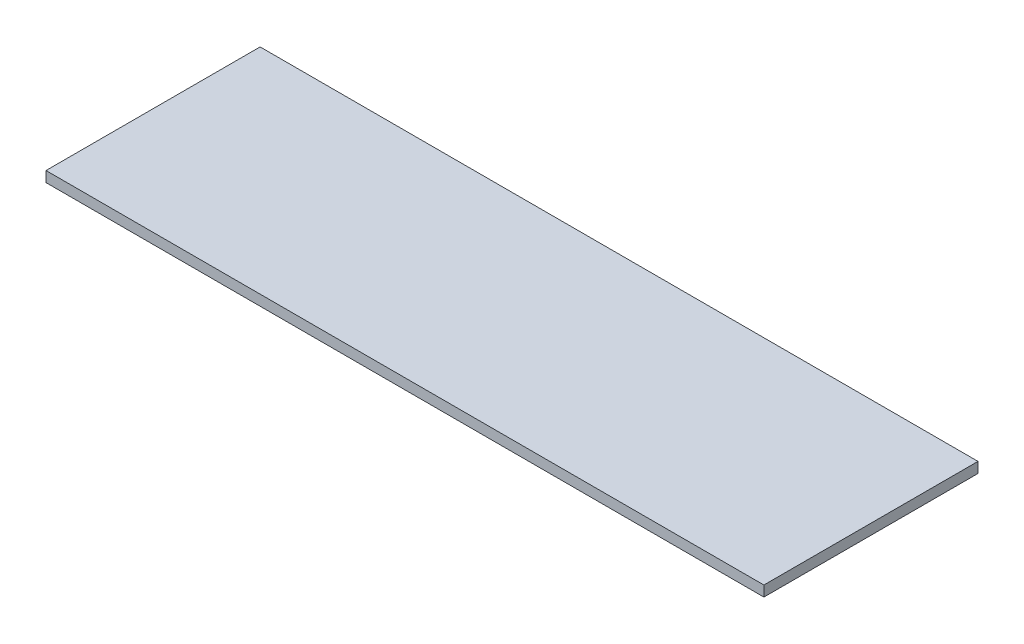
SolidWorks part; units mm, degrees
ref_plane "Front Plane" through (0, 0, 0) normal (0, 0, 1) x (1, 0, 0)
ref_plane "Top Plane" through (0, 0, 0) normal (0, 1, 0) x (1, 0, 0)
ref_plane "Right Plane" through (0, 0, 0) normal (1, 0, 0) x (0, 0, -1)
sketch "Sketch1" plane through (0, 0, 0) normal (0, 1, 0) x (1, 0, 0)
  line L1 (-171, 51) -> (171, 51)
  line L2 (-171, 51) -> (-171, -51)
  line L3 (-171, -51) -> (171, -51)
  line L4 (171, 51) -> (171, -51)
  line L5 (-171, 51) -> (171, -51) construction
  line L6 (-171, -51) -> (171, 51) construction
  point P0 (0, 0)
extrude "Boss-Extrude1" add sketch "Sketch1" along normal blind 5
